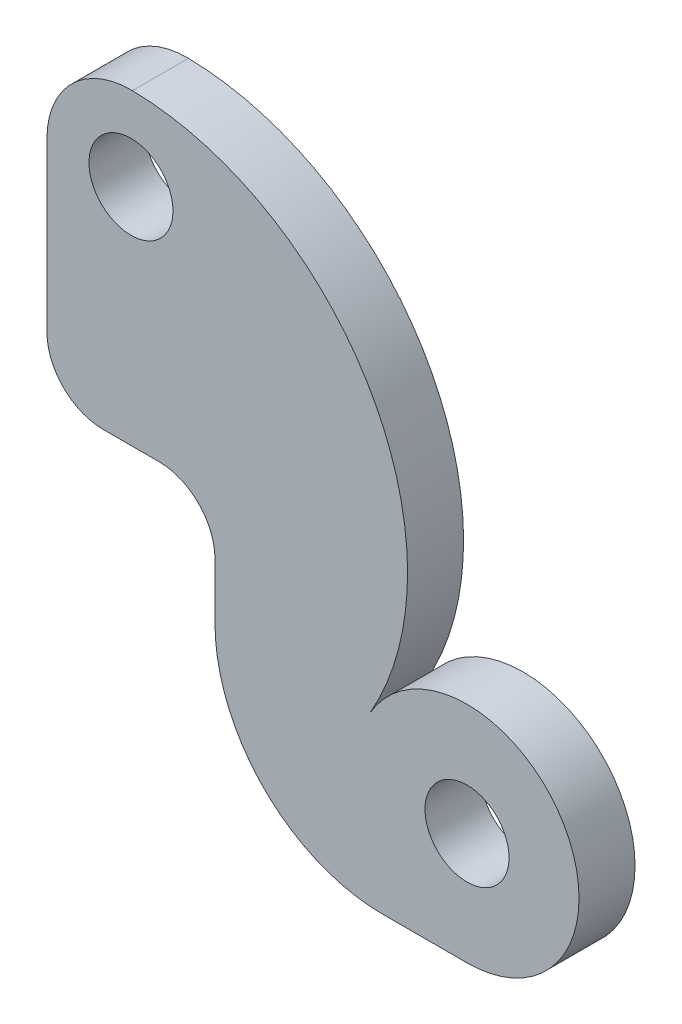
SolidWorks part; units mm, degrees
ref_plane "Front Plane" through (0, 0, 0) normal (0, 0, 1) x (1, 0, 0)
ref_plane "Top Plane" through (0, 0, 0) normal (0, 1, 0) x (1, 0, 0)
ref_plane "Right Plane" through (0, 0, 0) normal (1, 0, 0) x (0, 0, -1)
sketch "Sketch1" plane through (0, 0, 0) normal (0, 0, 1) x (1, 0, 0)
  line L0 (0, 0) -> (0, 50000) construction
  line L1 (0, 0) -> (50000, 0) construction
  line L2 (-30, 70) -> (-30, 40)
  line L3 (-20, 30) -> (-10, 30)
  line L4 (45, -20) -> (30, -20)
  line L5 (0, 10) -> (0, 20)
  circle A0 centre (45, 0) radius 7.5
  circle A1 centre (-15, 70) radius 7.5
  arc A2 (45, -20) -> (27.6804, 10.0016) centre (45, 0) ccw
  arc A3 (-14.7349, 84.9977) -> (-30, 70) centre (-15, 70) ccw
  arc A4 (0, 10) -> (30, -20) centre (30, 10) ccw
  arc A5 (-14.7349, 84.9977) -> (27.6804, 10.0016) centre (-15.6186, 35.0055) cw
  arc A6 (0, 20) -> (-10, 30) centre (-10, 20) ccw
  arc A7 (-20, 30) -> (-30, 40) centre (-20, 40) cw
  point P18 (0, -20)
  point P24 (-30, 30)
  dimension "D1" = 15
  dimension "D2" = 15
  dimension "D6" = 40
  dimension "D7" = 30
  dimension "D8" = 40
  dimension "D9" = 30
  dimension "D10" = 50
  dimension "D11" = 10
  dimension "D3" = 60
  dimension "D4" = 45
  dimension "D5" = 70
extrude "Boss-Extrude1" add sketch "Sketch1" along normal mid plane 10
